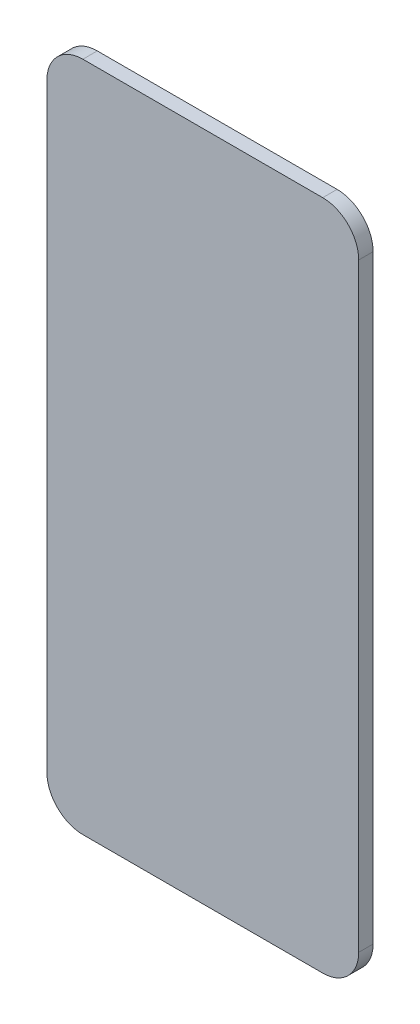
SolidWorks part; units mm, degrees
ref_plane "Front Plane" through (0, 0, 0) normal (0, 0, 1) x (1, 0, 0)
ref_plane "Top Plane" through (0, 0, 0) normal (0, 1, 0) x (1, 0, 0)
ref_plane "Right Plane" through (0, 0, 0) normal (1, 0, 0) x (0, 0, -1)
sketch "Sketch1" plane through (0, 0, 0) normal (0, 0, 1) x (1, 0, 0)
  line L1 (13, -28) -> (-13, -28)
  line L2 (13, -28) -> (13, 28)
  line L3 (13, 28) -> (-13, 28)
  line L4 (-13, -28) -> (-13, 28)
  line L5 (13, -28) -> (-13, 28) construction
  line L6 (13, 28) -> (-13, -28) construction
  point P0 (0, 0)
  dimension "D1" = 26
  dimension "D2" = 56
extrude "Boss-Extrude1" add sketch "Sketch1" along normal blind 1.2
fillet "Fillet1" radius 3 4 edges at (-13, -28, 0.6) (13, -28, 0.6) (-13, 28, 0.6) (13, 28, 0.6)
